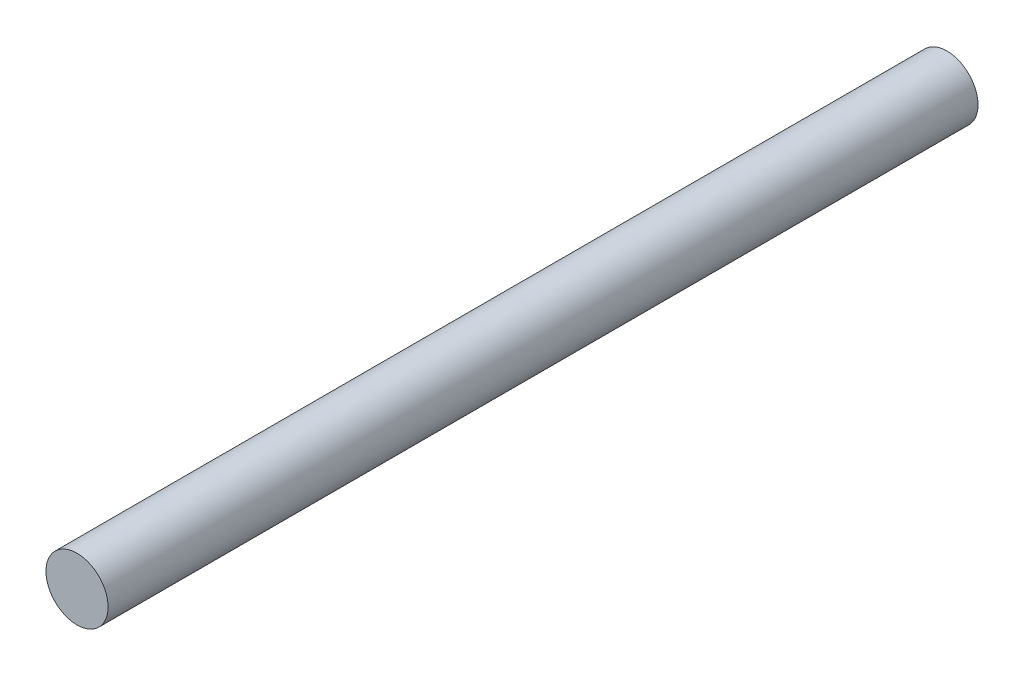
SolidWorks part; units mm, degrees
ref_plane "Front Plane" through (0, 0, 0) normal (0, 0, 1) x (1, 0, 0)
ref_plane "Top Plane" through (0, 0, 0) normal (0, 1, 0) x (1, 0, 0)
ref_plane "Right Plane" through (0, 0, 0) normal (1, 0, 0) x (0, 0, -1)
sketch "Sketch1" plane through (0, 0, 0) normal (0, 0, 1) x (1, 0, 0)
  circle A0 centre (0, 0) radius 0.25
  dimension "D1" = 0.5
extrude "Boss-Extrude1" add sketch "Sketch1" along normal blind 7
